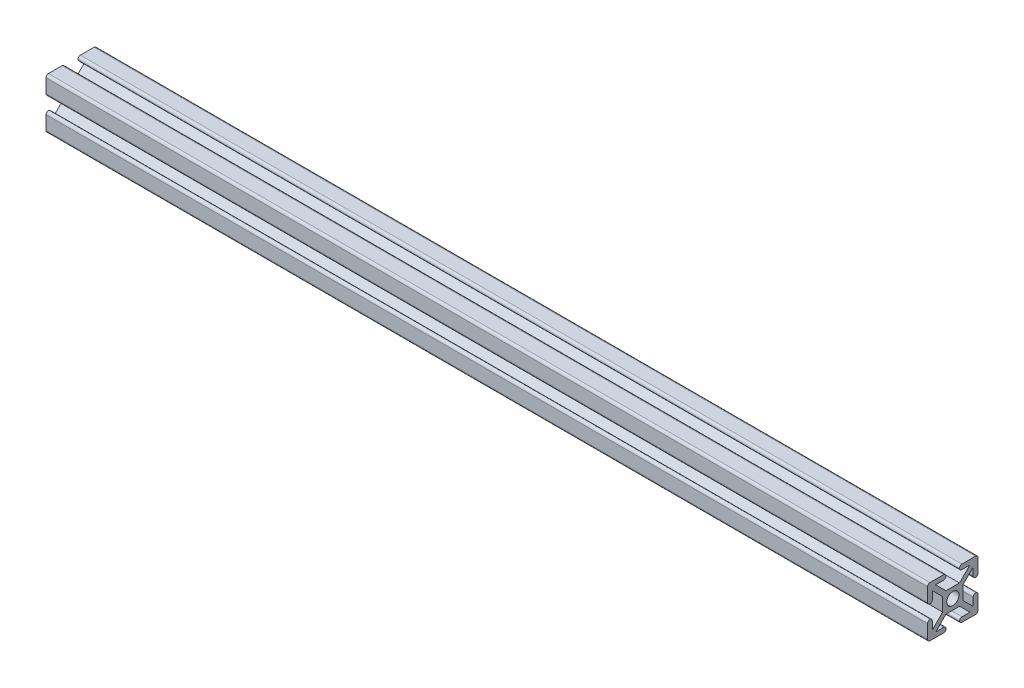
SolidWorks part; units mm, degrees
ref_plane "Alzado" through (0, 0, 0) normal (0, 0, 1) x (1, 0, 0)
ref_plane "Planta" through (0, 0, 0) normal (0, 1, 0) x (1, 0, 0)
ref_plane "Vista lateral" through (0, 0, 0) normal (1, 0, 0) x (0, 0, -1)
sketch "Croquis1" plane through (0, 0, 0) normal (1, 0, 0) x (0, 0, -1)
  line L0 (-15.3676, 26.4078) -> (-15.3676, 27.8328) construction
  line L1 (3.6852, 10.2578) -> (8.4102, 10.2578)
  line L2 (-16.7926, 35.9828) -> (-16.7926, 27.8328)
  line L3 (-15.3676, 37.4078) -> (-7.2176, 37.4078)
  line L4 (3.6324, 37.4078) -> (11.7824, 37.4078)
  line L5 (-11.8898, 10.2578) -> (-7.1648, 10.2578)
  line L6 (-7.7926, 26.4078) -> (-7.7926, 18.4078)
  line L7 (-16.7398, 16.9828) -> (-16.7398, 8.8328)
  line L8 (-15.3412, 7.4342) -> (-7.1648, 7.4078)
  line L9 (13.2074, 35.9828) -> (13.2074, 27.9365)
  line L10 (-13.9426, 32.5578) -> (-13.9426, 27.8328)
  line L11 (13.2074, 17.0865) -> (13.2074, 8.8328)
  line L12 (-5.7926, 35.9828) -> (-7.2176, 35.9828) construction
  line L13 (3.6852, 7.4078) -> (11.7824, 7.4078)
  line L14 (-11.9426, 34.5578) -> (-7.2176, 34.5578)
  line L15 (-13.9426, 16.9828) -> (-13.9426, 12.2578)
  line L16 (2.2074, 35.9828) -> (3.6324, 35.9828) construction
  line L17 (3.6324, 34.5578) -> (8.3574, 34.5578)
  line L18 (11.7824, 26.5115) -> (11.7824, 27.9365) construction
  line L19 (-5.7926, 28.4078) -> (-11.9426, 34.5578)
  line L20 (10.3574, 32.5578) -> (10.3574, 27.9365)
  line L21 (11.7824, 18.5115) -> (11.7824, 17.0865) construction
  line L22 (-7.7926, 26.4078) -> (-13.9426, 32.5578)
  line L23 (10.3574, 17.0865) -> (10.3574, 12.2578)
  line L24 (2.2602, 8.8328) -> (3.6852, 8.8328) construction
  line L25 (-7.7926, 18.4078) -> (-13.9426, 12.2578)
  line L26 (-5.7926, 28.4078) -> (2.2074, 28.4078)
  line L27 (2.2074, 28.4078) -> (8.3574, 34.5578)
  line L28 (-15.3412, 18.4078) -> (-15.3412, 16.9828) construction
  line L29 (-11.8898, 10.2578) -> (-5.7398, 16.4078)
  line L30 (-5.7398, 16.4078) -> (2.2602, 16.4078)
  line L31 (2.2602, 16.4078) -> (8.4102, 10.2578)
  line L32 (-5.7398, 8.8328) -> (-7.1648, 8.8328) construction
  line L33 (4.2074, 18.4078) -> (10.3574, 12.2578)
  line L34 (4.2074, 26.4078) -> (10.3574, 32.5578)
  line L35 (4.2074, 26.4078) -> (4.2074, 18.4078)
  circle A0 centre (-1.7398, 22.4078) radius 3.645
  arc A1 (-16.7926, 27.8328) -> (-13.9426, 27.8328) centre (-15.3676, 27.8328) ccw
  arc A2 (-7.2176, 34.5578) -> (-7.2176, 37.4078) centre (-7.2176, 35.9828) ccw
  arc A3 (3.6324, 37.4078) -> (3.6324, 34.5578) centre (3.6324, 35.9828) ccw
  arc A4 (10.3574, 27.9365) -> (13.2074, 27.9365) centre (11.7824, 27.9365) ccw
  arc A5 (13.2074, 17.0865) -> (10.3574, 17.0865) centre (11.7824, 17.0865) ccw
  arc A6 (3.6852, 10.2578) -> (3.6852, 7.4078) centre (3.6852, 8.8328) ccw
  arc A7 (-13.9426, 16.9828) -> (-16.7398, 16.9828) centre (-15.3412, 16.9828) ccw
  arc A8 (-7.1648, 7.4078) -> (-7.1648, 10.2578) centre (-7.1648, 8.8328) ccw
  arc A9 (-16.7398, 8.8328) -> (-15.3412, 7.4342) centre (-15.3412, 8.8328) ccw
  arc A10 (11.7824, 7.4078) -> (13.2074, 8.8328) centre (11.7824, 8.8328) ccw
  arc A11 (13.2074, 35.9828) -> (11.7824, 37.4078) centre (11.7824, 35.9828) ccw
  arc A12 (-15.3676, 37.4078) -> (-16.7926, 35.9828) centre (-15.3676, 35.9828) ccw
  dimension "D1" = 1.425
  dimension "D2" = 1.425
  dimension "D3" = 1.425
  dimension "D4" = 1.425
  dimension "D5" = 1.425
  dimension "D6" = 1.425
  dimension "D7" = 1.425
  dimension "D8" = 1.425
extrude "Saliente-Extruir1" add sketch "Croquis1" along normal blind 523.8
sketch "Croquis2" plane through (0, 0, 7.7926) normal (0, 0, 1) x (1, 0, 0)
  line L0 (0, 26.4078) -> (0, 18.4078) construction
  circle A0 centre (18.84, 22.4078) radius 4
  circle A1 centre (75.14, 22.4078) radius 4
  circle A2 centre (448.84, 22.4078) radius 4
  circle A3 centre (505.14, 22.4078) radius 4
  point P4 (0, 22.4078)
  dimension "D3" = 8
  dimension "D4" = 8
  dimension "D6" = 8
  dimension "D9" = 8
  dimension "D1" = 18.84
  dimension "D2" = 0
  dimension "D5" = 56.3
  dimension "D7" = 430
  dimension "D8" = 430
extrude "Cortar-Extruir1" cut sketch "Croquis2" against normal blind 523.8
